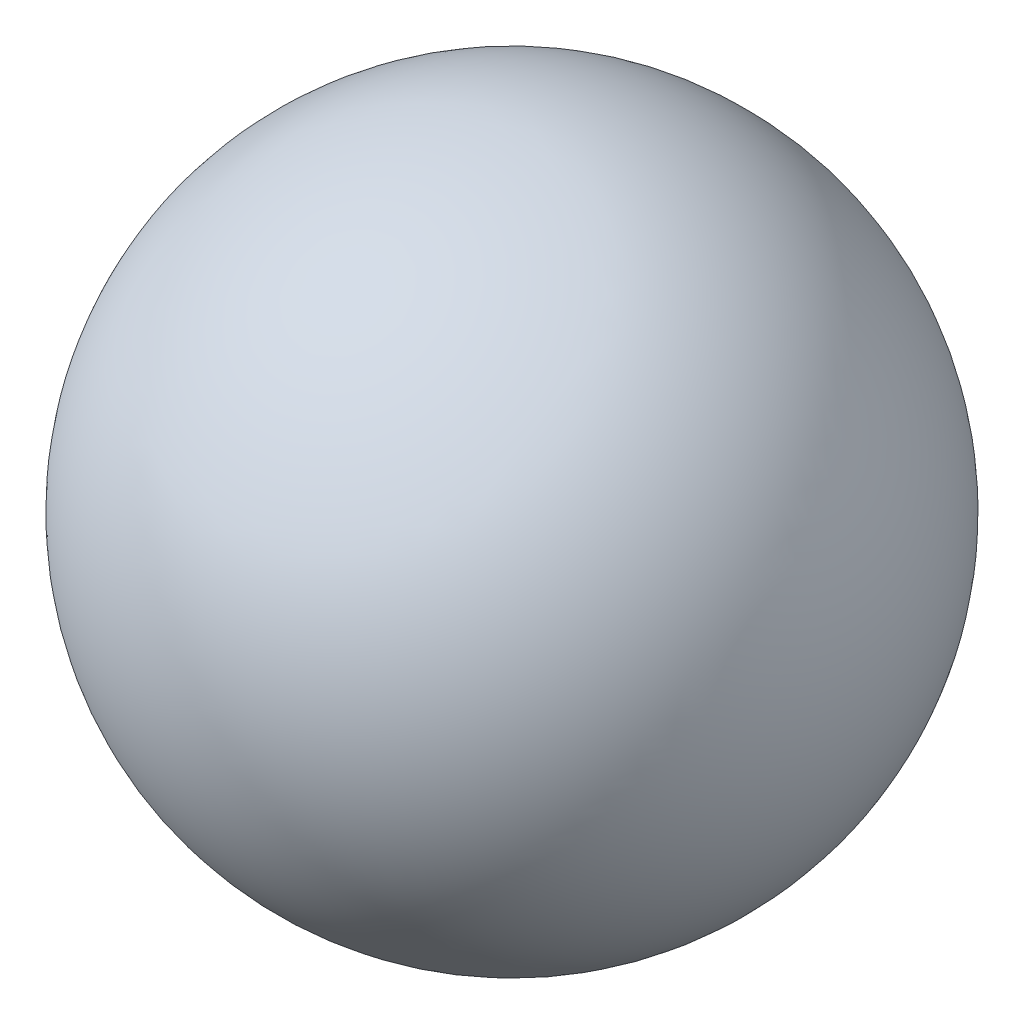
SolidWorks part; units mm, degrees
ref_plane "Piano frontale" through (0, 0, 0) normal (0, 0, 1) x (1, 0, 0)
ref_plane "Piano superiore" through (0, 0, 0) normal (0, 1, 0) x (1, 0, 0)
ref_plane "Piano destro" through (0, 0, 0) normal (1, 0, 0) x (0, 0, -1)
ref_plane "Piano1" through (0, 0, 0) normal (0, 0, 1) x (1, 0, 0)
sketch "Schizzo1" plane through (0, 0, 0) normal (0, 0, 1) x (1, 0, 0)
  line L0 (24.5, 58.75) -> (3.5, 58.75)
  line L1 (24.5, 58.75) -> (3.5, 58.75) construction
  arc A0 (3.5, 58.75) -> (24.5, 58.75) centre (14, 58.75) cw
revolve "Rivoluzione1" add sketch "Schizzo1" angle 360 about L1
